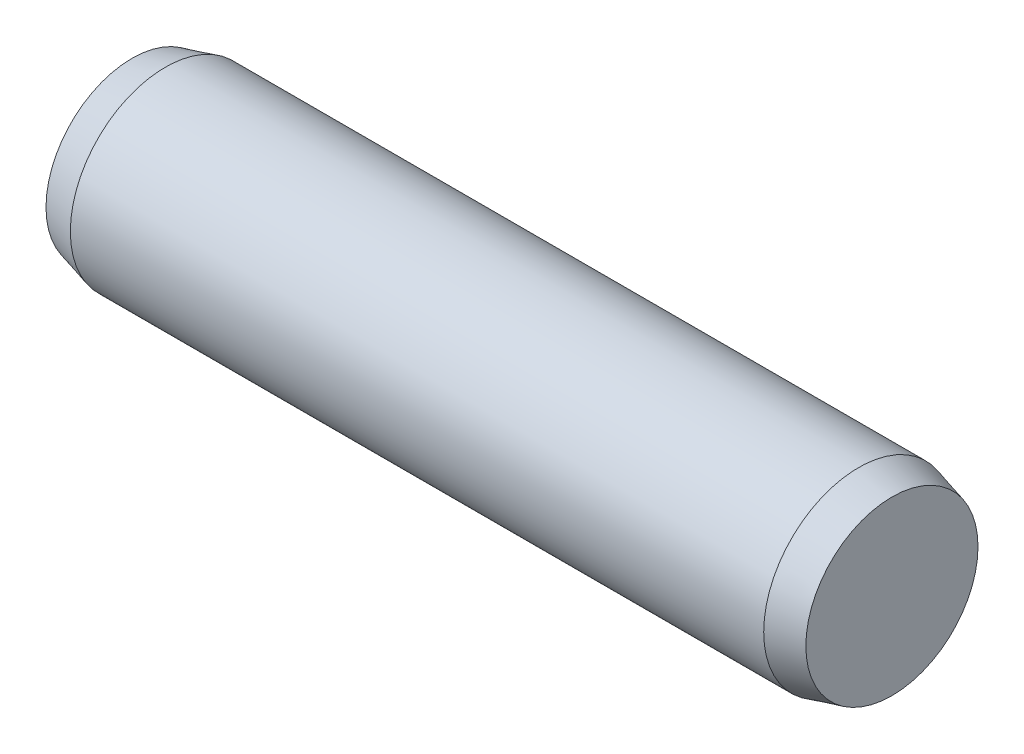
SolidWorks part; units mm, degrees
ref_plane "Front Plane" through (0, 0, 0) normal (0, 0, 1) x (1, 0, 0)
ref_plane "Top Plane" through (0, 0, 0) normal (0, 1, 0) x (1, 0, 0)
ref_plane "Right Plane" through (0, 0, 0) normal (1, 0, 0) x (0, 0, -1)
sketch "Sketch1" plane through (0, 0, 0) normal (0, 0, 1) x (1, 0, 0)
  line L0 (-3.65, 0) -> (3.65, 0) construction
  line L1 (3.65, 1) -> (3.65, -1) construction
  line L2 (-3.65, 1) -> (-3.65, -1) construction
  line L3 (4, 1) -> (4, -1) construction
  line L4 (-4, 1) -> (-4, -1) construction
  line L5 (-3.65, 0) -> (-4, 0) construction
  line L6 (3.65, 0) -> (4, 0) construction
  dimension "Dia" = 2
  dimension "C" = 0.35
  dimension "D1" = 0.35
  dimension "Length" = 8
sketch "Sketch2" plane through (0, 0, 0) normal (1, 0, 0) x (0, 0, -1)
  circle A0 centre (0, 0) radius 1
extrude "Extrude1" add sketch "Sketch2" against normal up to vertex (3.65 mm away) and the other way up to vertex (3.65 mm away) up to point (-3.65, 1, 0) other way up to point (3.65, 1, 0)
sketch "Sketch3" plane through (3.65, 0, 0) normal (1, 0, 0) x (0, 0, -1)
  circle A1 centre (0, 0) radius 1
  circle A2 centre (0, 0) radius 1
  dimension "D1" = 0
extrude "Extrude2" add sketch "Sketch3" along normal up to vertex (0.35 mm away) draft 15 up to point (4, 0, 0)
sketch "Sketch4" plane through (-3.65, 0, 0) normal (-1, 0, 0) x (0, 0, 1)
  circle A1 centre (0, 0) radius 1
  circle A2 centre (0, 0) radius 1
  dimension "D1" = 0
extrude "Extrude3" add sketch "Sketch4" along normal up to vertex (0.35 mm away) draft 15 up to point (-4, 0, 0)
equation "\"D1@Sketch1\" = \"C@Sketch1\""
